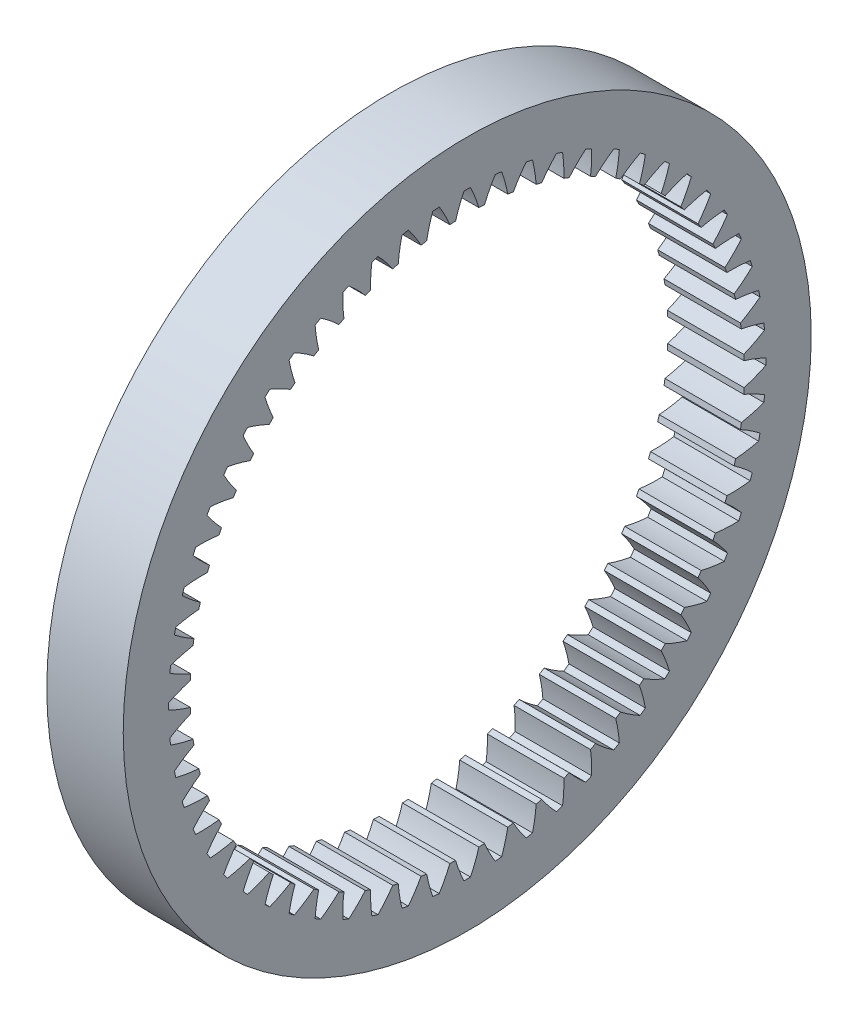
SolidWorks part; units mm, degrees
ref_plane "Plane1" through (0, 0, 0) normal (0, 0, 1) x (1, 0, 0)
ref_plane "Plane2" through (0, 0, 0) normal (0, 1, 0) x (1, 0, 0)
ref_plane "Plane3" through (0, 0, 0) normal (1, 0, 0) x (0, 0, -1)
other "Configuration Table"
sketch "HoldingSke" plane through (0, 0, 0) normal (0, 1, 0) x (1, 0, 0)
  line L0 (0, 0) -> (1, -1.7321)
  line L1 (-15, 0) -> (100, 0) construction
  line L2 (0, 0) -> (-2.1039, 2.3779)
  line L3 (0, 0) -> (-11.863, 4.5341)
  line L4 (0, 0) -> (4.318, 7.479)
  line L5 (0, 0) -> (-23.7986, -8.8762)
  line L6 (0, 0) -> (-10.5278, -7.1032)
  line L7 (-2.1039, 2.3779) -> (3.3635, 27.1825)
  line L8 (-76.2, 2.8779) -> (-54.61, 2.8779)
  line L9 (-71.009, 38.7566) -> (-53.1078, 45.2721)
  line L10 (-76.2, 71.12) -> (104.1128, 71.12)
  line L11 (0, 0) -> (-4, 0)
  line L12 (-76.2, 101.6) -> (-76.181, 101.6)
  line L13 (24.9733, 27.94) -> (52.9518, 28.4284)
  line L14 (24.9733, 27.94) -> (24.9743, 27.94)
  line L15 (24.9733, 27.94) -> (100.4006, 29.5858)
  circle A0 centre (0, 0) radius 18
  circle A1 centre (0, 0) radius 12.7
  circle A2 centre (0, 0) radius 12.7
  dimension "MHD" = 25.4
  dimension "Hub_dia" = 25.4
  dimension "Diameter" = 36
  dimension "Num_teeth" = 60
  dimension "Pitch" = 2
  dimension "Overall_len" = 25.4
  dimension "Show_teeth" = 60
  dimension "Thickness" = 12.7
  dimension "OAL" = 25.4001
  dimension "T_dim" = 21.59
  dimension "Ap" = 20
  dimension "H" = 19.05
  dimension "Pitch_radius" = 180.3128
  dimension "Width" = 4
  dimension "Backlash" = 0.019
  dimension "Addendum_fac" = 1
  dimension "Dedendum_fac" = 1.25
  dimension "Clearance_fac" = 0.25
  dimension "Dedendum_add" = 0.001
  dimension "Module" = 0.5
sketch "BasProSke" plane through (0, 0, 0) normal (0, 1, 0) x (1, 0, 0)
  line L0 (-10, 0) -> (60, 0) construction
  line L1 (0, 14.5) -> (0, 18)
  line L2 (0, 14.5) -> (4, 14.5)
  line L3 (4, 14.5) -> (4, 18)
  line L4 (4, 18) -> (0, 18)
  dimension "Diameter" = 36
  dimension "Thickness" = 4
  dimension "Inside_diameter" = 29
revolve "Base-Revolve" add sketch "BasProSke" angle 360 about L0
sketch "TooCutSke" plane through (0, 0, 0) normal (1, 0, 0) x (0, 0, -1)
  line L3 (0.4402, 14.9935) -> (0.4402, 53.6633) construction
  line L4 (0, 0) -> (0, 59.563) construction
  line L5 (0, 0) -> (-3.576, 68.2339) construction
  line L6 (-6.5816, 12.3583) -> (37.127, 14.649) construction
  circle A0 centre (0, 0) radius 15 construction
  circle A1 centre (0, 0) radius 15.626 construction
  circle A2 centre (0, 0) radius 12.6859 construction
  circle A3 centre (0, 0) radius 14.4746 construction
  arc A4 (0.6175, 14.4614) -> (0.1695, 15.6251) centre (-6.5816, 12.3583) ccw
  arc A5 (0.6175, 14.4614) -> (-0.6175, 14.4614) centre (0, 0) ccw
  arc A6 (0.1695, 15.6251) -> (-0.1695, 15.6251) centre (0, 0) ccw
  arc A7 (-0.1695, 15.6251) -> (-0.6175, 14.4614) centre (6.5816, 12.3583) ccw
  dimension "Pitch_dia" = 30
  dimension "Base_dia" = 25.3717
  dimension "Root_dia" = 31.252
  dimension "Overcut_dia" = 28.9492
  dimension "Flank_rad" = 7.5
  dimension "Half_ang" = 3
  dimension "Half_CT" = 0.4402
extrude "ToothCut" cut sketch "TooCutSke" along normal through all
fillet "Breaks" [suppressed] radius 0.05
fillet "RootFillets" [suppressed] radius 0.126
pattern_circular "TeethCuts" count 60 every 6 about axis through (-10, 0, 0) along (1, 0, 0) of "RootFillets", "Breaks", "ToothCut"
equation "' \"Module@HoldingSke\" = 6.35"
equation "' \"Num_teeth@HoldingSke\" = 24"
equation "' \"Ap@HoldingSke\" =  14.5"
equation "' \"Ap@HoldingSke\" = 14.5"
equation "' \"Width@HoldingSke\" = 12"
equation "' \"Diameter@HoldingSke\" = 8 * 25.4"
equation "' \"Show_teeth@HoldingSke\" = 100"
equation "' \"Backlash@HoldingSke\" = 0.009 * 25.4"
equation "' \"Addendum_fac@HoldingSke\" = 1.0"
equation "' \"Dedendum_fac@HoldingSke\" = 1.25"
equation "' \"Dedendum_add@HoldingSke\" = 0.00005 * 25.4"
equation "' \"Clearance_fac@HoldingSke\" = 0.25"
equation "\"Pitch@HoldingSke\" = 1 / \"Module@HoldingSke\" "
equation "\"Overcut_dia@TooCutSke\" = (\"Num_teeth@HoldingSke\" - 2 * \"Addendum_fac@HoldingSke\") / \"Pitch@HoldingSke\" - 0.002 * 25.4"
equation "\"Pitch_dia@TooCutSke\" = \"Num_teeth@HoldingSke\" / \"Pitch@HoldingSke\""
equation "\"Base_dia@TooCutSke\" = \"Num_teeth@HoldingSke\" / \"Pitch@HoldingSke\" * cos((\"Ap@HoldingSke\"  * 3.14159265 / 180)) * 0.90"
equation "\"Root_dia@TooCutSke\" = \"Num_teeth@HoldingSke\"  / \"Pitch@HoldingSke\" + 2 *  \"Dedendum_fac@HoldingSke\"/ \"Pitch@HoldingSke\" + \"Dedendum_add@HoldingSke\" * 2"
equation "\"Half_ang@TooCutSke\" = 180 / \"Num_teeth@HoldingSke\""
equation "\"Half_CT@TooCutSke\" = \"Num_teeth@HoldingSke\" / \"Pitch@HoldingSke\" * sin((3.14159265 / 2 / \"Num_teeth@HoldingSke\")) / 2 + 10 * \"Backlash@HoldingSke\" / 4"
equation "\"Flank_rad@TooCutSke\" = \"Num_teeth@HoldingSke\" / \"Pitch@HoldingSke\" / 4"
equation "\"Radius@RootFillets\"= \"Clearance_fac@HoldingSke\" / \"Pitch@HoldingSke\" + \"Dedendum_add@HoldingSke\""
equation "\"Break_rad@Breaks\" = 0.02 / \"Pitch@HoldingSke\" * 5"
equation "\"Num_teeth@TeethCuts\" = int( \"Show_teeth@HoldingSke\" ) + 1"
equation "\"Num_teeth@TeethCuts\" = ((sgn( \"Num_teeth@TeethCuts\" - \"Num_teeth@HoldingSke\" )-1)*( \"Num_teeth@TeethCuts\" - \"Num_teeth@HoldingSke\" ))/-2+ \"Num_teeth@HoldingSke\""
equation "\"Num_teeth@TeethCuts\" = ((sgn( \"Num_teeth@TeethCuts\" - 2.0)+1)*( \"Num_teeth@TeethCuts\" - 2.0))/2 +2.0"
equation "\"Angle@TeethCuts\" = 360.0 / \"Num_teeth@HoldingSke\""
equation "\"Diameter@BasProSke\" = \"Num_teeth@HoldingSke\"  / \"Pitch@HoldingSke\" + 2 *  \"Dedendum_fac@HoldingSke\"/ \"Pitch@HoldingSke\" + \"Dedendum_add@HoldingSke\" * 2 + 0.002 * 25.4"
equation "\"Diameter@BasProSke\" = ((sgn( \"Diameter@BasProSke\"  - \"Diameter@HoldingSke\" )+1)*( \"Diameter@BasProSke\"  - \"Diameter@HoldingSke\" ))/2 + \"Diameter@HoldingSke\""
equation "\"Inside_diameter@BasProSke\" =  (\"Num_teeth@HoldingSke\" - 2 * \"Addendum_fac@HoldingSke\") / \"Pitch@HoldingSke\" "
equation "\"Thickness@BasProSke\"  = \"Width@HoldingSke\""
